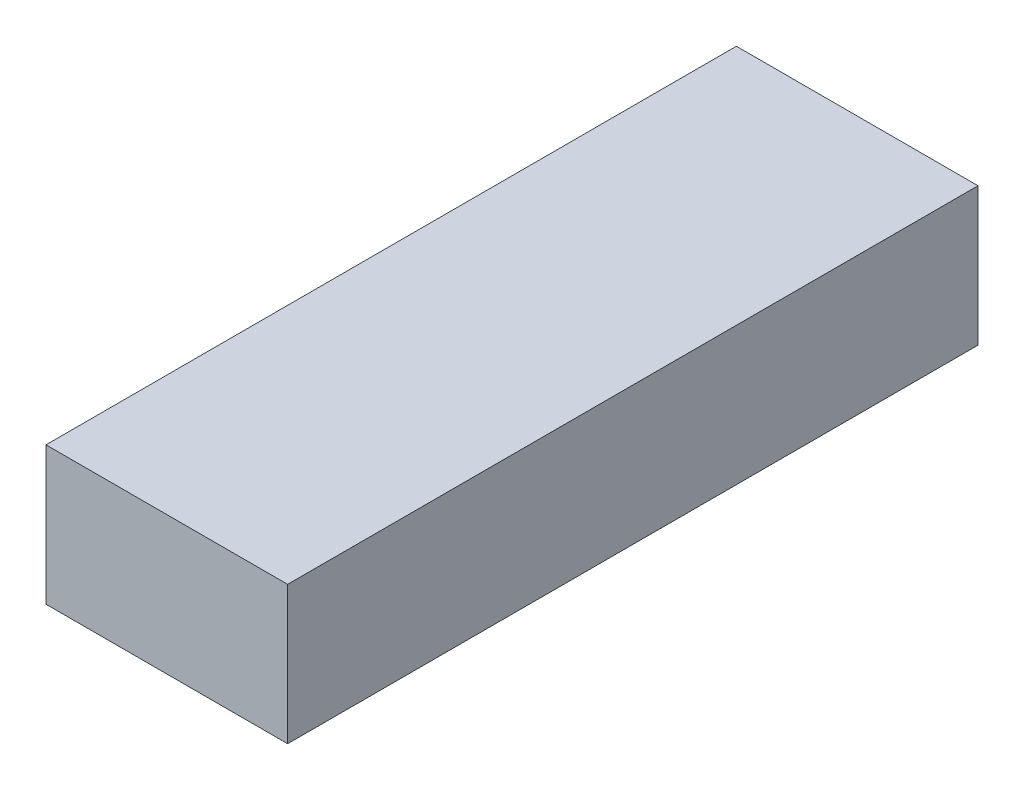
SolidWorks part; units mm, degrees
ref_plane "Front" through (0, 0, 0) normal (0, 0, 1) x (1, 0, 0)
ref_plane "Top" through (0, 0, 0) normal (0, 1, 0) x (1, 0, 0)
ref_plane "Right" through (0, 0, 0) normal (1, 0, 0) x (0, 0, -1)
sketch "Sketch1" plane through (0, 0, 0) normal (0, 0, 1) x (1, 0, 0)
  line L1 (0, 0) -> (-4.445, 0)
  line L2 (0, 0) -> (0, 2.54)
  line L3 (0, 2.54) -> (-4.445, 2.54)
  line L4 (-4.445, 0) -> (-4.445, 2.54)
  dimension "D1" = 4.445
  dimension "D2" = 2.54
extrude "Boss-Extrude1" add sketch "Sketch1" along normal blind 12.7
sketch "Sketch2" plane through (0, 0, 0) normal (1, 0, 0) x (0, 0, -1)
  line L0 (-12.7, 0) -> (-12.7, 2.54) construction
  line L1 (-12.7, 2.54) -> (0, 2.54) construction
  circle A0 centre (-11.43, 1.27) radius 0.4445
  dimension "D1" = 0.889
  dimension "D2" = 1.27
  dimension "D3" = 1.27
